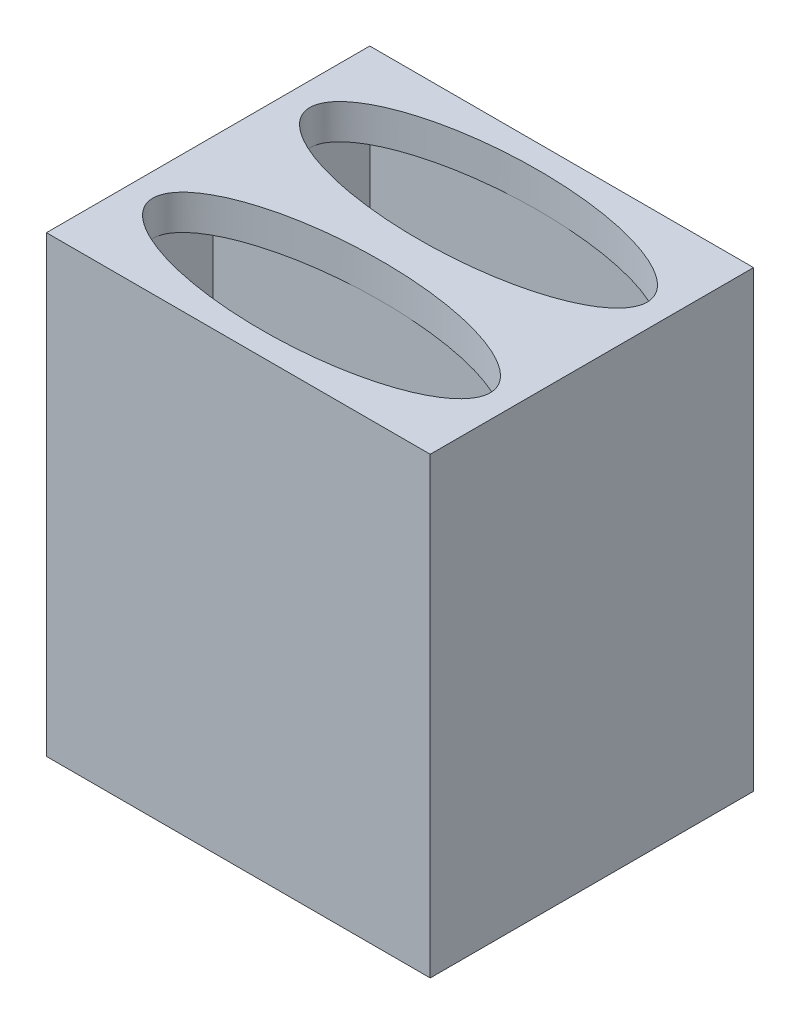
SolidWorks part; units mm, degrees
ref_plane "Front Plane" through (0, 0, 0) normal (0, 0, 1) x (1, 0, 0)
ref_plane "Top Plane" through (0, 0, 0) normal (0, 1, 0) x (1, 0, 0)
ref_plane "Right Plane" through (0, 0, 0) normal (1, 0, 0) x (0, 0, -1)
sketch "草图1" plane through (0, 0, 0) normal (0, 1, 0) x (1, 0, 0)
  line L0 (-16.5, -7.15) -> (-16.5, 7.15)
  line L1 (-14.5, -5.15) -> (14.5, -5.15)
  line L2 (-14.5, -5.15) -> (-14.5, 5.15)
  line L3 (-14.5, 5.15) -> (14.5, 5.15)
  line L4 (14.5, -5.15) -> (14.5, 5.15)
  line L5 (-14.5, -5.15) -> (14.5, 5.15) construction
  line L6 (-14.5, 5.15) -> (14.5, -5.15) construction
  line L7 (-16.5, 7.15) -> (16.5, 7.15)
  line L8 (16.5, -7.15) -> (16.5, 7.15)
  line L9 (-16.5, -7.15) -> (16.5, -7.15)
  point P0 (0, 0)
  dimension "D1" = 10.3
  dimension "D2" = 29
  dimension "D3" = 2
extrude "凸台-拉伸2" add sketch "草图1" along normal blind 36
sketch "草图2" plane through (0, 36, 0) normal (0, 1, 0) x (1, 0, 0)
  line L0 (14.5, -5.15) -> (14.5, 5.15) construction
  line L1 (16.5, 7.15) -> (-16.5, 7.15)
  line L2 (16.5, 7.15) -> (16.5, -7.15)
  line L3 (16.5, -7.15) -> (-16.5, -7.15)
  line L4 (-16.5, 7.15) -> (-16.5, -7.15)
  line L5 (-14.5, -5.15) -> (14.5, -5.15) construction
  ellipse E0 centre (0, 0) end of major axis (14.5, 0) minor radius 5.15
  point P7 (14.5, 0)
  point P16 (0, -3.8232)
  point P17 (0, -5.15)
extrude "凸台-拉伸3" add sketch "草图2" along normal blind 3
pattern_linear "阵列(线性)1" count 2 spacing 13.5 along (0, 0, -1) of "凸台-拉伸2", "凸台-拉伸3"
